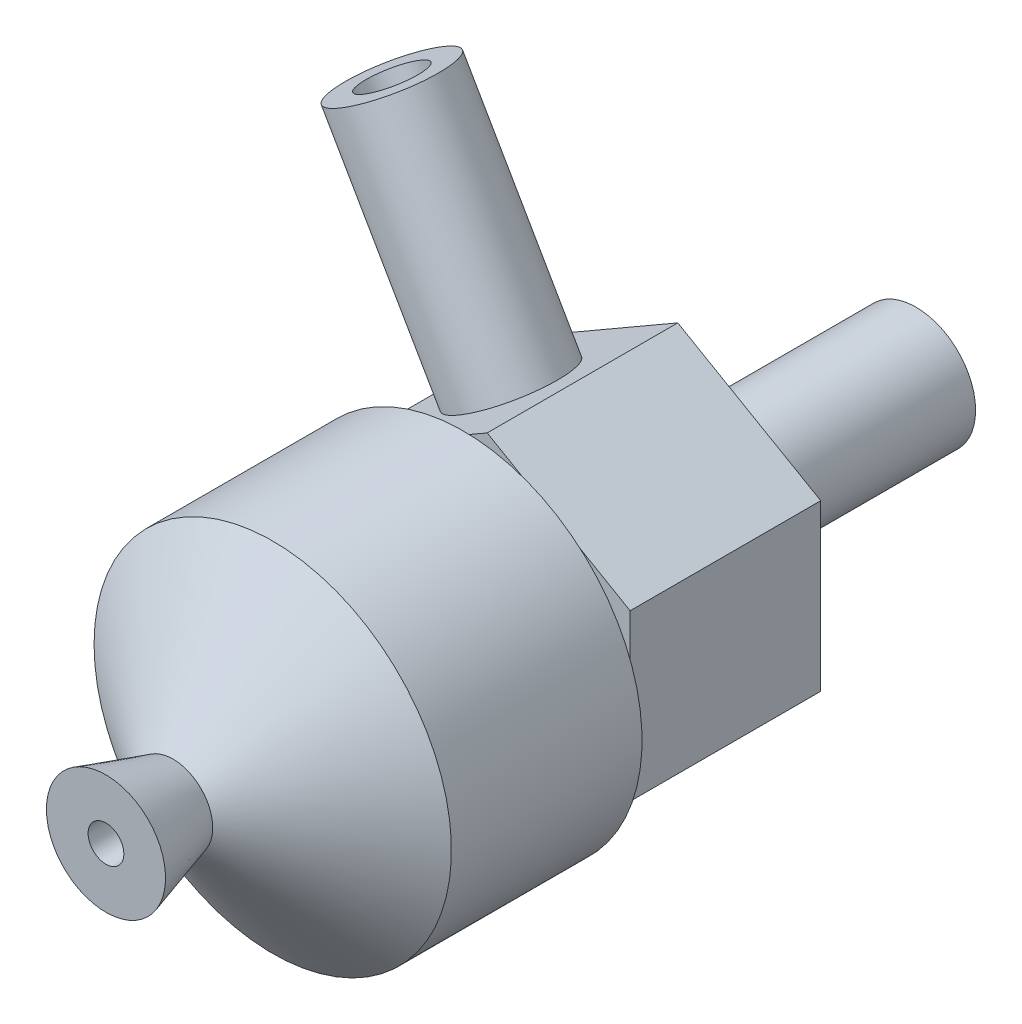
SolidWorks part; units mm, degrees
material "SKD11淬火HRC56-60"
ref_plane "前基準面" through (0, 0, 0) normal (0, 0, 1) x (1, 0, 0)
ref_plane "上基準面" through (0, 0, 0) normal (0, 1, 0) x (1, 0, 0)
ref_plane "右基準面" through (0, 0, 0) normal (1, 0, 0) x (0, 0, -1)
sketch "草图1" plane through (0, 0, 0) normal (0, 0, 1) x (1, 0, 0)
  circle A0 centre (0, 0) radius 2.5
  dimension "D1" = 5
extrude "凸台-拉伸1" add sketch "草图1" along normal blind 10
cosmetic thread "装饰螺纹线1" parameters "D1"=8, "D2"=4.2
sketch "草图2" plane through (0, 0, 10) normal (0, 0, 1) x (1, 0, 0)
  line L0 (0, 0) -> (0, 4.3308) construction
  line L1 (6, 3.4641) -> (0, 6.9282)
  line L2 (0, 6.9282) -> (-6, 3.4641)
  line L3 (-6, 3.4641) -> (-6, -3.4641)
  line L4 (-6, -3.4641) -> (0, -6.9282)
  line L5 (0, -6.9282) -> (6, -3.4641)
  line L6 (6, -3.4641) -> (6, 3.4641)
  circle A0 centre (0, 0) radius 6 construction
  dimension "D1" = 12
extrude "凸台-拉伸2" add sketch "草图2" along normal blind 8
sketch "草图3" plane through (0, 0, 18) normal (0, 0, 1) x (1, 0, 0)
  circle A0 centre (0, 0) radius 2
  dimension "D1" = 4
extrude "凸台-拉伸3" add sketch "草图3" along normal blind 1
sketch "草图4" plane through (0, 0, 0) normal (0, 1, 0) x (1, 0, 0)
  line L0 (0, -19) -> (0, -28.7825) construction
  line L1 (-2, -19) -> (2, -19) construction
  line L2 (0, -19) -> (7.5, -19)
  line L3 (7.5, -19) -> (7.5, -27)
  line L4 (7.5, -27) -> (1.6642, -31.1834)
  line L5 (1.6642, -31.1834) -> (2.5, -34)
  line L6 (2.5, -34) -> (0, -34)
  line L7 (0, -19) -> (0, -34)
  line L9 (6, -10) -> (0, -10) construction
  dimension "D1" = 2.5
  dimension "D2" = 24
  dimension "D3" = 7.5
  dimension "D4" = 8
revolve "旋转1" add sketch "草图4" angle 360 about L0
sketch "草图5" plane through (0, 0, 34) normal (0, 0, 1) x (1, 0, 0)
  circle A0 centre (0, 0) radius 0.75
  dimension "D1" = 1.5
extrude "切除-拉伸1" cut sketch "草图5" against normal blind 15
sketch "草图6" plane through (-3, 5.1962, 0) normal (-0.5, 0.866, 0) x (0.866, 0.5, 0)
  line L0 (0, -8.5) -> (0, -18) construction
  line L1 (3.4641, -18) -> (-3.4641, -18) construction
  line L3 (0, -14) -> (3.4641, -14) construction
  line L4 (3.4641, -18) -> (3.4641, -10) construction
  circle A0 centre (0, -14) radius 2.25
  dimension "D1" = 4.5
extrude "凸台-拉伸4" add sketch "草图6" along normal blind 10
sketch "草图7" plane through (-8, 13.8564, 0) normal (-0.5, 0.866, 0) x (0.866, 0.5, 0)
  circle A0 centre (0, -14) radius 1.25
  dimension "D1" = 2.5
extrude "切除-拉伸2" cut sketch "草图7" against normal blind 22
